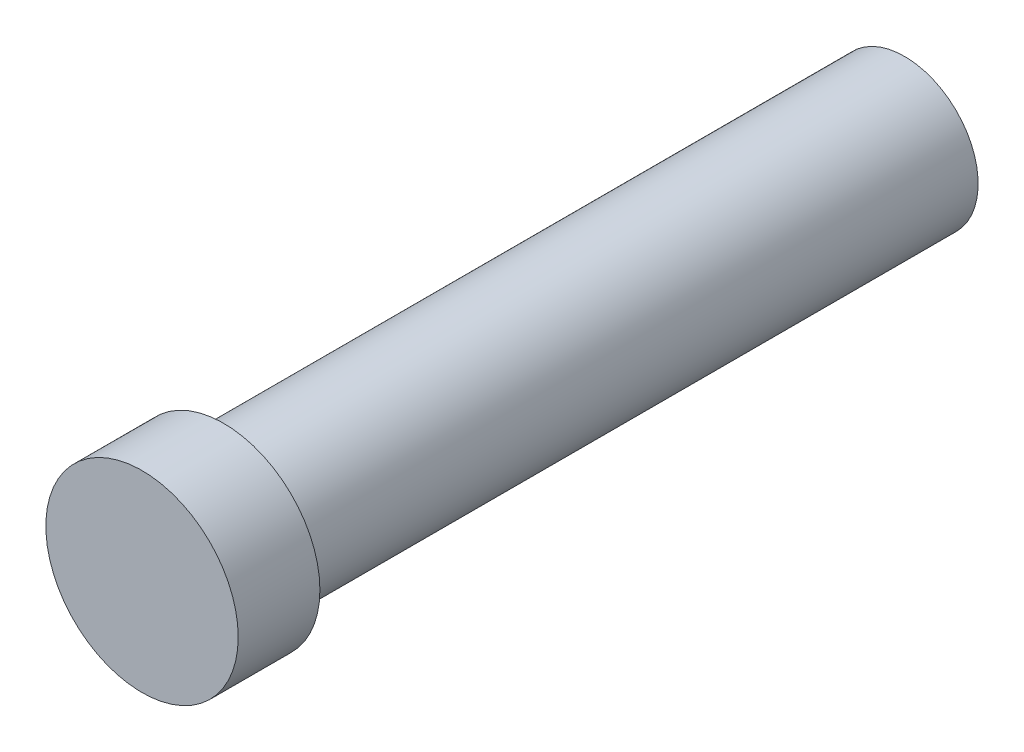
SolidWorks part; units mm, degrees
ref_plane "Front Plane" through (0, 0, 0) normal (0, 0, 1) x (1, 0, 0)
ref_plane "Top Plane" through (0, 0, 0) normal (0, 1, 0) x (1, 0, 0)
ref_plane "Right Plane" through (0, 0, 0) normal (1, 0, 0) x (0, 0, -1)
sketch "Sketch1" plane through (0, 0, 0) normal (0, 0, 1) x (1, 0, 0)
  circle A0 centre (0, 0) radius 1.35
  dimension "D1" = 2.7
extrude "Boss-Extrude1" add sketch "Sketch1" along normal blind 14
sketch "Sketch2" plane through (0, 0, 14) normal (0, 0, 1) x (1, 0, 0)
  circle A0 centre (0, 0) radius 1.7657
extrude "Boss-Extrude2" add sketch "Sketch2" against normal blind 1.5
